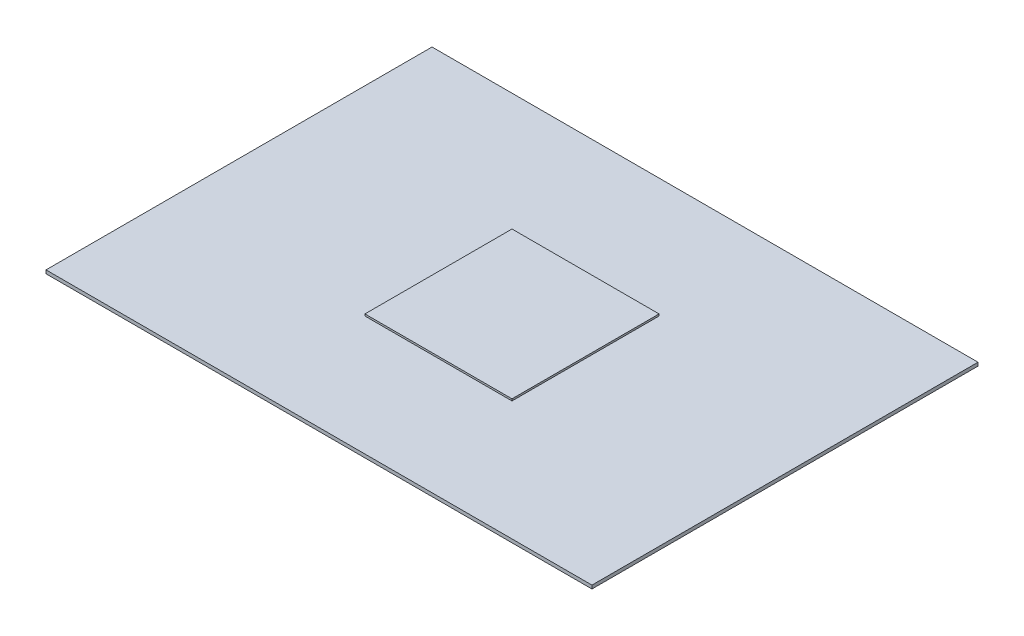
SolidWorks part; units mm, degrees
ref_plane "前视基准面" through (0, 0, 0) normal (0, 0, 1) x (1, 0, 0)
ref_plane "上视基准面" through (0, 0, 0) normal (0, 1, 0) x (1, 0, 0)
ref_plane "右视基准面" through (0, 0, 0) normal (1, 0, 0) x (0, 0, -1)
other "Configuration Table"
sketch "草图1" plane through (0, 0, 0) normal (0, 1, 0) x (1, 0, 0)
  line L1 (-148.5, -105) -> (148.5, -105)
  line L2 (-148.5, -105) -> (-148.5, 105)
  line L3 (-148.5, 105) -> (148.5, 105)
  line L4 (148.5, -105) -> (148.5, 105)
  line L5 (-148.5, -105) -> (148.5, 105) construction
  line L6 (-148.5, 105) -> (148.5, -105) construction
  point P0 (0, 0)
  dimension "D1" = 297
  dimension "D2" = 210
extrude "凸台-拉伸1" add sketch "草图1" along normal blind 1.8518
sketch "草图2" plane through (0, 1.8518, 0) normal (0, 1, 0) x (1, 0, 0)
  line L1 (-40, -40) -> (40, -40)
  line L2 (-40, -40) -> (-40, 40)
  line L3 (-40, 40) -> (40, 40)
  line L4 (40, -40) -> (40, 40)
  line L5 (-40, -40) -> (40, 40) construction
  line L6 (-40, 40) -> (40, -40) construction
  point P0 (0, 0)
  dimension "D1" = 80
  dimension "D2" = 80
extrude "凸台-拉伸2" add sketch "草图2" along normal blind 1
